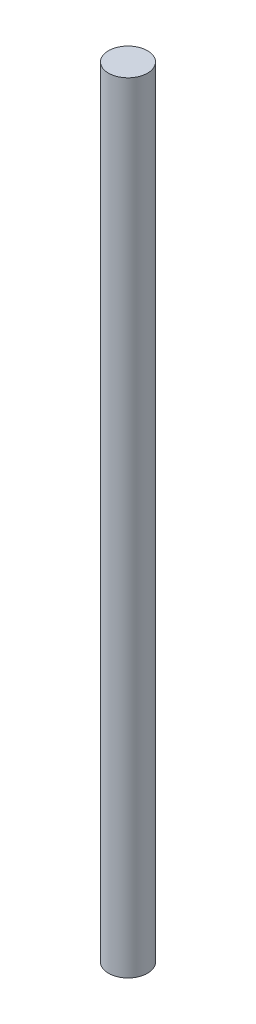
SolidWorks part; units mm, degrees
ref_plane "Front Plane" through (0, 0, 0) normal (0, 0, 1) x (1, 0, 0)
ref_plane "Top Plane" through (0, 0, 0) normal (0, 1, 0) x (1, 0, 0)
ref_plane "Right Plane" through (0, 0, 0) normal (1, 0, 0) x (0, 0, -1)
sketch "Sketch1" plane through (0, 0, 0) normal (0, 1, 0) x (1, 0, 0)
  circle A0 centre (0, 0) radius 10
  dimension "D1" = 20
extrude "Extrude1" add sketch "Sketch1" along normal blind 400
sketch "Sketch2" plane through (0, 0, 0) normal (0, -1, 0) x (1, 0, 0)
  point P0 (0, 0)
sketch "Sketch3" plane through (0, 400, 0) normal (0, 1, 0) x (-1, 0, 0)
  point P0 (0, 0)
sketch "Sketch4" plane through (0, 0, 0) normal (0, -1, 0) x (1, 0, 0)
  point P0 (0, 0)
